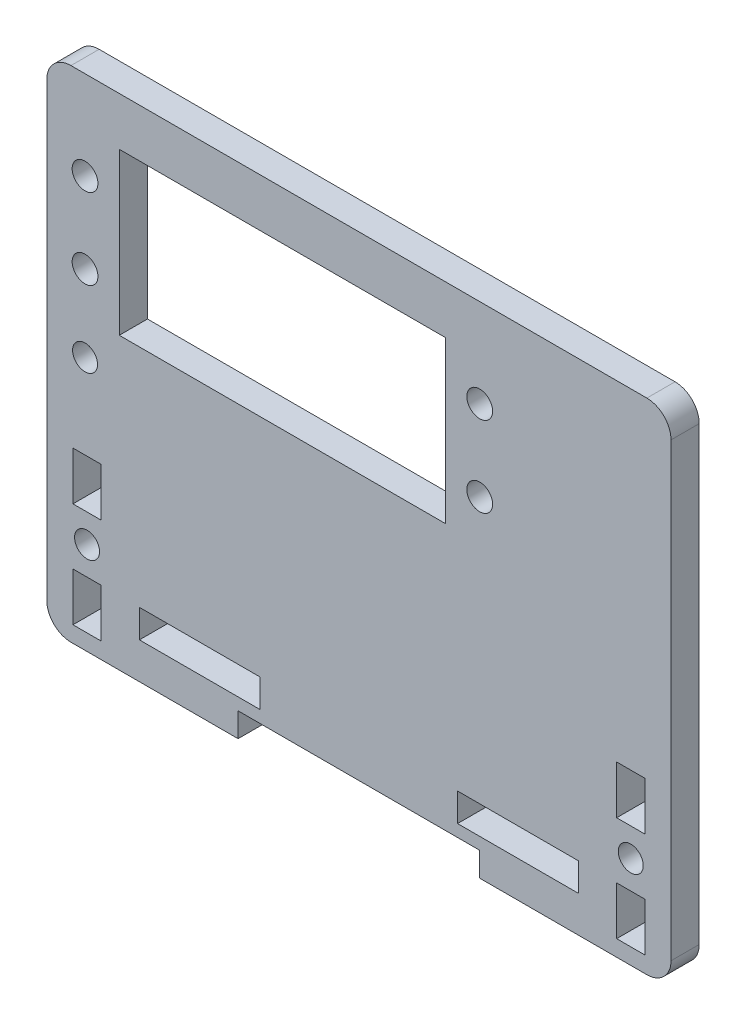
SolidWorks part; units mm, degrees
material "Balsa"
ref_plane "Front Plane" through (0, 0, 0) normal (0, 0, 1) x (1, 0, 0)
ref_plane "Top Plane" through (0, 0, 0) normal (0, 1, 0) x (1, 0, 0)
ref_plane "Right Plane" through (0, 0, 0) normal (1, 0, 0) x (0, 0, -1)
sketch "Sketch1" plane through (0, 0, 0) normal (0, 0, 1) x (1, 0, 0)
  line L1 (-35.75, -31) -> (35.75, -31)
  line L2 (-38.75, -28) -> (-38.75, 28)
  line L3 (-35.75, 31) -> (35.75, 31)
  line L4 (38.75, -28) -> (38.75, 28)
  line L5 (0, 31) -> (0, -31) construction
  line L6 (-38.75, 0) -> (38.75, 0) construction
  line L7 (-29.75, 5) -> (10.75, 5)
  line L8 (-29.75, 5) -> (-29.75, 25)
  line L9 (-29.75, 25) -> (10.75, 25)
  line L10 (10.75, 5) -> (10.75, 25)
  arc A0 (35.75, 31) -> (38.75, 28) centre (35.75, 28) cw
  arc A1 (35.75, -31) -> (38.75, -28) centre (35.75, -28) ccw
  arc A2 (-35.75, -31) -> (-38.75, -28) centre (-35.75, -28) cw
  arc A3 (-38.75, 28) -> (-35.75, 31) centre (-35.75, 28) cw
  point P0 (0, 0)
  point P8 (38.75, -31)
  point P12 (-38.75, -31)
  dimension "D2" = 3
  dimension "D3" = 62
  dimension "D1" = 28
  dimension "D4" = 40.5
  dimension "D5" = 20
  dimension "D6" = 9
  dimension "D7" = 6
extrude "Boss-Extrude1" add sketch "Sketch1" along normal blind 3.5
sketch "Sketch2" plane through (0, 0, 3.5) normal (0, 0, 1) x (1, 0, 0)
  line L0 (-38.75, -19.5) -> (38.75, -19.5) construction
  line L1 (-35.75, -31) -> (35.75, -31) construction
  line L2 (38.75, -28) -> (38.75, 28) construction
  line L3 (-38.75, 28) -> (-38.75, -28) construction
  line L4 (33.75, -29.922) -> (33.75, 0) construction
  line L5 (32, -16) -> (35.5, -16)
  line L6 (32, -16) -> (32, -10)
  line L7 (32, -10) -> (35.5, -10)
  line L8 (35.5, -16) -> (35.5, -10)
  line L9 (35.5, -23) -> (32, -23)
  line L10 (35.5, -23) -> (35.5, -29)
  line L11 (35.5, -29) -> (32, -29)
  line L12 (32, -23) -> (32, -29)
  line L13 (0, 10.4666) -> (0, -9.03) construction
  line L14 (-35.5, -23) -> (-32, -23)
  line L15 (-32, -23) -> (-32, -29)
  line L16 (-35.5, -29) -> (-32, -29)
  line L17 (-35.5, -23) -> (-35.5, -29)
  line L18 (-32, -16) -> (-35.5, -16)
  line L19 (-32, -16) -> (-32, -10)
  line L20 (-32, -10) -> (-35.5, -10)
  line L21 (-35.5, -16) -> (-35.5, -10)
  circle A1 centre (33.75, -19.5) radius 1.55
  circle A2 centre (-33.75, -19.5) radius 1.55
  dimension "D2" = 0
  dimension "D9" = 3.1
  dimension "D1" = 11.5
  dimension "D3" = 6
  dimension "D4" = 3.5
  dimension "D5" = 6
  dimension "D6" = 19
  dimension "D8" = 5
extrude "Cut-Extrude1" cut sketch "Sketch2" against normal through all
sketch "Sketch3" plane through (0, 0, 3.5) normal (0, 0, 1) x (1, 0, 0)
  line L0 (-32, -23) -> (32, -23) construction
  line L1 (0, 0) -> (0, -31) construction
  line L2 (-27.25, -23) -> (-12.25, -23)
  line L3 (-27.25, -23) -> (-27.25, -26.5)
  line L4 (-27.25, -26.5) -> (-12.25, -26.5)
  line L5 (-12.25, -23) -> (-12.25, -26.5)
  line L6 (-35.75, -31) -> (35.75, -31) construction
  line L8 (27.25, -23) -> (27.25, -26.5)
  line L9 (27.25, -23) -> (12.25, -23)
  line L10 (12.25, -23) -> (12.25, -26.5)
  line L11 (27.25, -26.5) -> (12.25, -26.5)
  dimension "D1" = 24.5
  dimension "D2" = 15
  dimension "D3" = 3.5
extrude "Cut-Extrude2" cut sketch "Sketch3" against normal through all
sketch "Sketch4" plane through (0, 0, 3.5) normal (0, 0, 1) x (1, 0, 0)
  line L0 (-32.7283, 15) -> (20.2148, 15) construction
  line L1 (10.75, 25) -> (-29.75, 25) construction
  line L2 (-9.5, -1.2649) -> (-9.5, 28.2785) construction
  line L3 (-29.75, 5) -> (10.75, 5) construction
  line L4 (-29.75, 25) -> (-29.75, 5) construction
  line L5 (10.75, 5) -> (10.75, 25) construction
  line L7 (-34, 10) -> (15, 10) construction
  line L8 (-34, 10) -> (-34, 20) construction
  line L9 (-34, 20) -> (15, 20) construction
  line L10 (15, 10) -> (15, 20) construction
  line L11 (-9.5, 20) -> (-9.5, 10) construction
  line L12 (-34, 15) -> (15, 15) construction
  circle A0 centre (15, 20) radius 1.6
  circle A1 centre (15, 10) radius 1.6
  circle A2 centre (-34, 10) radius 1.6
  circle A3 centre (-34, 20) radius 1.6
  point P12 (-9.5, 15)
  dimension "D3" = 3.2
  dimension "D4" = 4.25
  dimension "D1" = 10
  dimension "D2" = 49
  dimension "D5" = 4.25
extrude "Cut-Extrude3" cut sketch "Sketch4" against normal through all both and the other way through all
sketch "Sketch5" plane through (0, 0, 3.5) normal (0, 0, 1) x (1, 0, 0)
  line L0 (-34, 31) -> (-34, -31) construction
  line L3 (35.75, 31) -> (-35.75, 31) construction
  line L6 (-35.75, -31) -> (35.75, -31) construction
  circle A2 centre (-34, 0.5) radius 1.55
  circle A7 centre (-34, 10) radius 1.6 construction
  dimension "D1" = 9.5
extrude "Cut-Extrude4" cut sketch "Sketch5" against normal up to next contours A2
sketch "Sketch6" plane through (0, 0, 3.5) normal (0, 0, 1) x (1, 0, 0)
  line L0 (0, 0) -> (0, -32.3805) construction
  line L1 (-35.75, -31) -> (35.75, -31) construction
  line L2 (-15, -28) -> (15, -28)
  line L3 (-15, -28) -> (-15, -31)
  line L4 (-15, -31) -> (15, -31)
  line L5 (15, -28) -> (15, -31)
  line L6 (-15, -28) -> (15, -31) construction
  line L7 (-15, -31) -> (15, -28) construction
  point P3 (0, -29.5)
  dimension "D1" = 30
  dimension "D2" = 3
extrude "Cut-Extrude5" cut sketch "Sketch6" against normal blind 10
